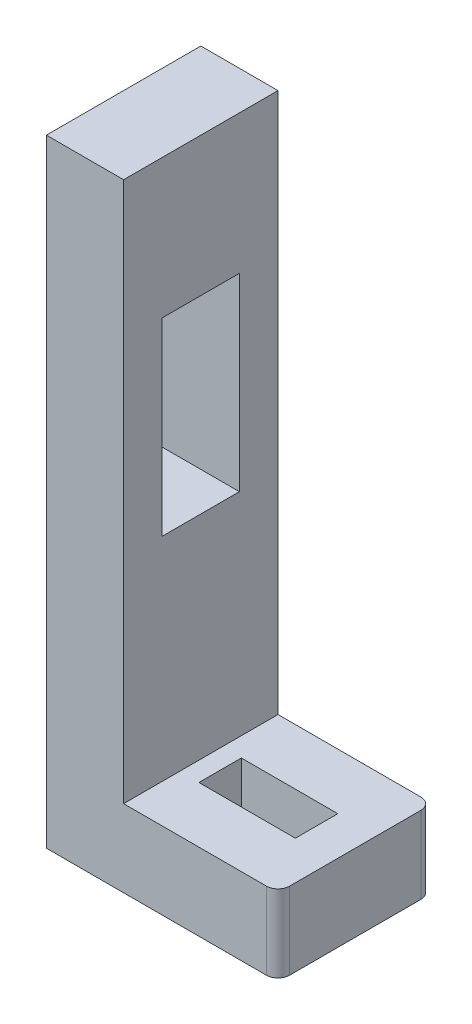
SolidWorks part; units mm, degrees
ref_plane "Front Plane" through (0, 0, 0) normal (0, 0, 1) x (1, 0, 0)
ref_plane "Top Plane" through (0, 0, 0) normal (0, 1, 0) x (1, 0, 0)
ref_plane "Right Plane" through (0, 0, 0) normal (1, 0, 0) x (0, 0, -1)
sketch "Sketch1" plane through (0, 0, 0) normal (0, 0, 1) x (1, 0, 0)
  line L0 (0, 0) -> (0, 160)
  line L1 (0, 160) -> (20, 160)
  line L2 (20, 160) -> (20, 20)
  line L3 (20, 20) -> (60, 20)
  line L4 (60, 20) -> (60, 0)
  line L5 (60, 0) -> (0, 0)
  dimension "D1" = 160
  dimension "D2" = 60
  dimension "D3" = 20
  dimension "D4" = 20
extrude "Boss-Extrude1" add sketch "Sketch1" along normal blind 40
fillet "Fillet1" radius 3 2 edges at (60, 10, 0) (60, 10, 40)
sketch "Sketch2" plane through (0, 20, 0) normal (0, 1, 0) x (1, 0, 0)
  line L0 (20, -40) -> (20, 0) construction
  line L1 (25, -14.5) -> (50, -14.5)
  line L2 (25, -14.5) -> (25, -25.5)
  line L3 (25, -25.5) -> (50, -25.5)
  line L4 (50, -14.5) -> (50, -25.5)
  line L5 (60, -37) -> (60, -3) construction
  point P6 (25, -20)
  point P9 (60, -20)
  point P10 (50, -20)
  dimension "D1" = 11
  dimension "D2" = 25
  dimension "D3" = 5
extrude "Cut-Extrude1" cut sketch "Sketch2" against normal through all
sketch "Sketch3" plane through (20, 0, 0) normal (1, 0, 0) x (0, 0, -1)
  line L0 (-40, 160) -> (0, 160) construction
  line L1 (-30, 124) -> (-10, 124)
  line L2 (-30, 124) -> (-30, 75)
  line L3 (-30, 75) -> (-10, 75)
  line L4 (-10, 124) -> (-10, 75)
  point P6 (-20, 160)
  point P7 (-20, 124)
  dimension "D1" = 20
  dimension "D2" = 49
  dimension "D3" = 36
extrude "Cut-Extrude2" cut sketch "Sketch3" against normal through all
